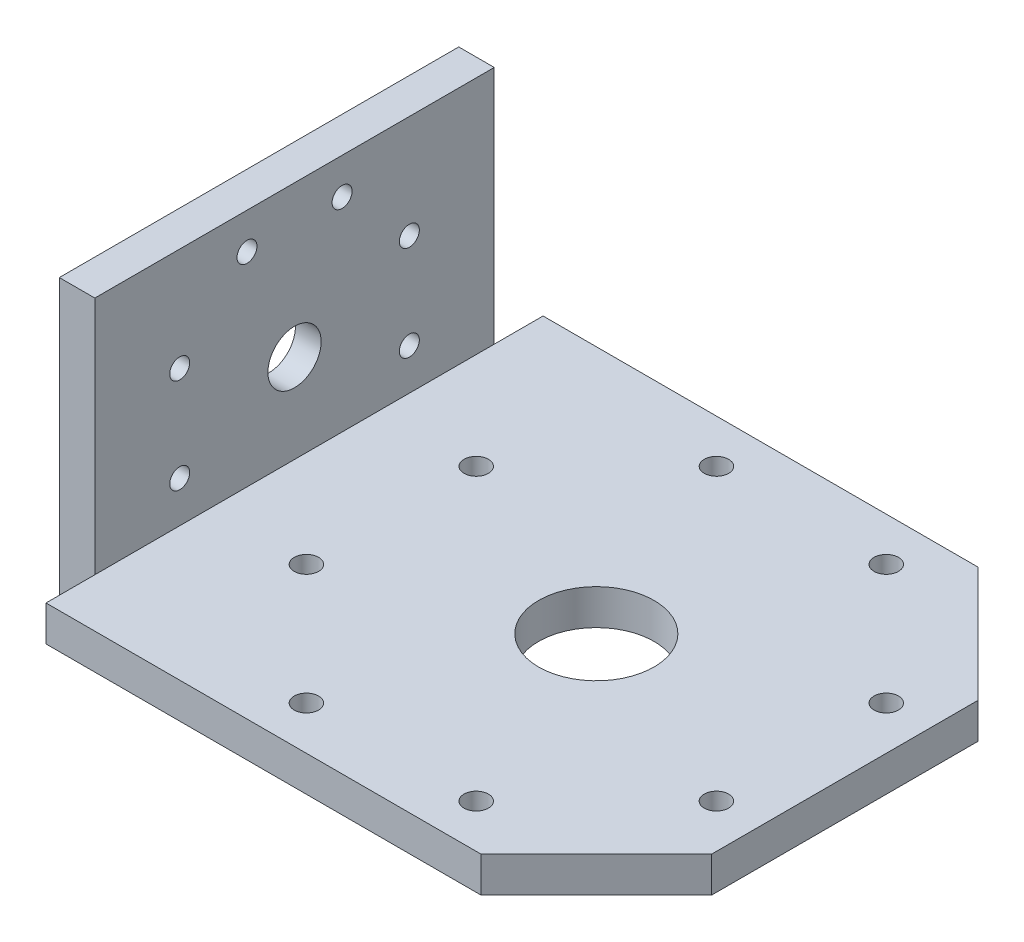
SolidWorks part; units mm, degrees
ref_plane "Front Plane" through (0, 0, 0) normal (0, 0, 1) x (1, 0, 0)
ref_plane "Top Plane" through (0, 0, 0) normal (0, 1, 0) x (1, 0, 0)
ref_plane "Right Plane" through (0, 0, 0) normal (1, 0, 0) x (0, 0, -1)
ref_plane "PL_Back_Plate_base" through (-76, 0, 0) normal (1, 0, 0) x (0, 0, -1)
sketch "SK_Back_Plate" plane through (-76, 0, 0) normal (1, 0, 0) x (0, 0, -1)
  line L0 (45, -36) -> (45, 34)
  line L1 (45, 34) -> (-45, 34)
  line L2 (-45, 34) -> (-45, -36)
  line L3 (-45, -36) -> (45, -36)
  circle A0 centre (25.8686, 10.7151) radius 2.25
  circle A1 centre (10.7151, 25.8686) radius 2.25
  circle A2 centre (-10.7151, 25.8686) radius 2.25
  circle A3 centre (-25.8686, 10.7151) radius 2.25
  circle A4 centre (-25.8686, -10.7151) radius 2.25
  circle A5 centre (-10.7151, -25.8686) radius 2.25
  circle A6 centre (10.7151, -25.8686) radius 2.25
  circle A7 centre (25.8686, -10.7151) radius 2.25
  circle A8 centre (0, 0) radius 6
  dimension "D9_SK_Back_Plate" = 4.5
  dimension "D12_SK_Back_Plate" = 4.5
  dimension "D15_SK_Back_Plate" = 4.5
  dimension "D18_SK_Back_Plate" = 4.5
  dimension "D21_SK_Back_Plate" = 4.5
  dimension "D24_SK_Back_Plate" = 4.5
  dimension "D27_SK_Back_Plate" = 4.5
  dimension "D30_SK_Back_Plate" = 4.5
  dimension "D33_SK_Back_Plate" = 12
  dimension "P1" = 45
  dimension "P2" = 36
  dimension "P3" = 45
  dimension "P4" = 34
  dimension "P5" = 45
  dimension "P6" = 34
  dimension "P7" = 45
  dimension "P8" = 36
  dimension "P10" = 25.8686
  dimension "P11" = 10.7151
  dimension "P13" = 10.7151
  dimension "P14" = 25.8686
  dimension "P16" = 10.7151
  dimension "P17" = 25.8686
  dimension "P19" = 25.8686
  dimension "P20" = 10.7151
  dimension "P22" = 25.8686
  dimension "P23" = 10.7151
  dimension "P25" = 10.7151
  dimension "P26" = 25.8686
  dimension "P28" = 10.7151
  dimension "P29" = 25.8686
  dimension "P31" = 25.8686
  dimension "P32" = 10.7151
extrude "Back_Plate" add sketch "SK_Back_Plate" along normal blind 8
ref_plane "PL_Roll_Pilot_Recess_base" through (-76, 0, 0) normal (1, 0, 0) x (0, 0, -1)
sketch "SK_Roll_Pilot_Recess" plane through (-76, 0, 0) normal (1, 0, 0) x (0, 0, -1)
  circle A0 centre (0, 0) radius 22.15
  dimension "D1_SK_Roll_Pilot_Recess" = 44.3
extrude "Roll_Pilot_Recess" cut sketch "SK_Roll_Pilot_Recess" along normal blind 2.2
ref_plane "PL_Medial_Plate_base" through (0, -28, 0) normal (0, 1, 0) x (1, 0, 0)
sketch "SK_Medial_Plate" plane through (0, -28, 0) normal (0, 1, 0) x (1, 0, 0)
  line L0 (-68, 56) -> (30, 56)
  line L1 (30, 56) -> (56, 30)
  line L2 (56, 30) -> (56, -30)
  line L3 (56, -30) -> (30, -56)
  line L4 (30, -56) -> (-68, -56)
  line L5 (-68, -56) -> (-68, 56)
  circle A0 centre (46.194, 19.1342) radius 2.75
  circle A1 centre (19.1342, 46.194) radius 2.75
  circle A2 centre (-19.1342, 46.194) radius 2.75
  circle A3 centre (-46.194, 19.1342) radius 2.75
  circle A4 centre (-46.194, -19.1342) radius 2.75
  circle A5 centre (-19.1342, -46.194) radius 2.75
  circle A6 centre (19.1342, -46.194) radius 2.75
  circle A7 centre (46.194, -19.1342) radius 2.75
  circle A8 centre (0, 0) radius 13
  dimension "D13_SK_Medial_Plate" = 5.5
  dimension "D16_SK_Medial_Plate" = 5.5
  dimension "D19_SK_Medial_Plate" = 5.5
  dimension "D22_SK_Medial_Plate" = 5.5
  dimension "D25_SK_Medial_Plate" = 5.5
  dimension "D28_SK_Medial_Plate" = 5.5
  dimension "D31_SK_Medial_Plate" = 5.5
  dimension "D34_SK_Medial_Plate" = 5.5
  dimension "D37_SK_Medial_Plate" = 26
  dimension "P1" = 68
  dimension "P2" = 56
  dimension "P3" = 30
  dimension "P4" = 56
  dimension "P5" = 56
  dimension "P6" = 30
  dimension "P7" = 56
  dimension "P8" = 30
  dimension "P9" = 30
  dimension "P10" = 56
  dimension "P11" = 68
  dimension "P12" = 56
  dimension "P14" = 46.194
  dimension "P15" = 19.1342
  dimension "P17" = 19.1342
  dimension "P18" = 46.194
  dimension "P20" = 19.1342
  dimension "P21" = 46.194
  dimension "P23" = 46.194
  dimension "P24" = 19.1342
  dimension "P26" = 46.194
  dimension "P27" = 19.1342
  dimension "P29" = 19.1342
  dimension "P30" = 46.194
  dimension "P32" = 19.1342
  dimension "P33" = 46.194
  dimension "P35" = 46.194
  dimension "P36" = 19.1342
extrude "Medial_Plate" add sketch "SK_Medial_Plate" along normal blind 8
equation "\"Roll_face_x\" = -76"
equation "\"Pitch_rear_y\" = -20"
